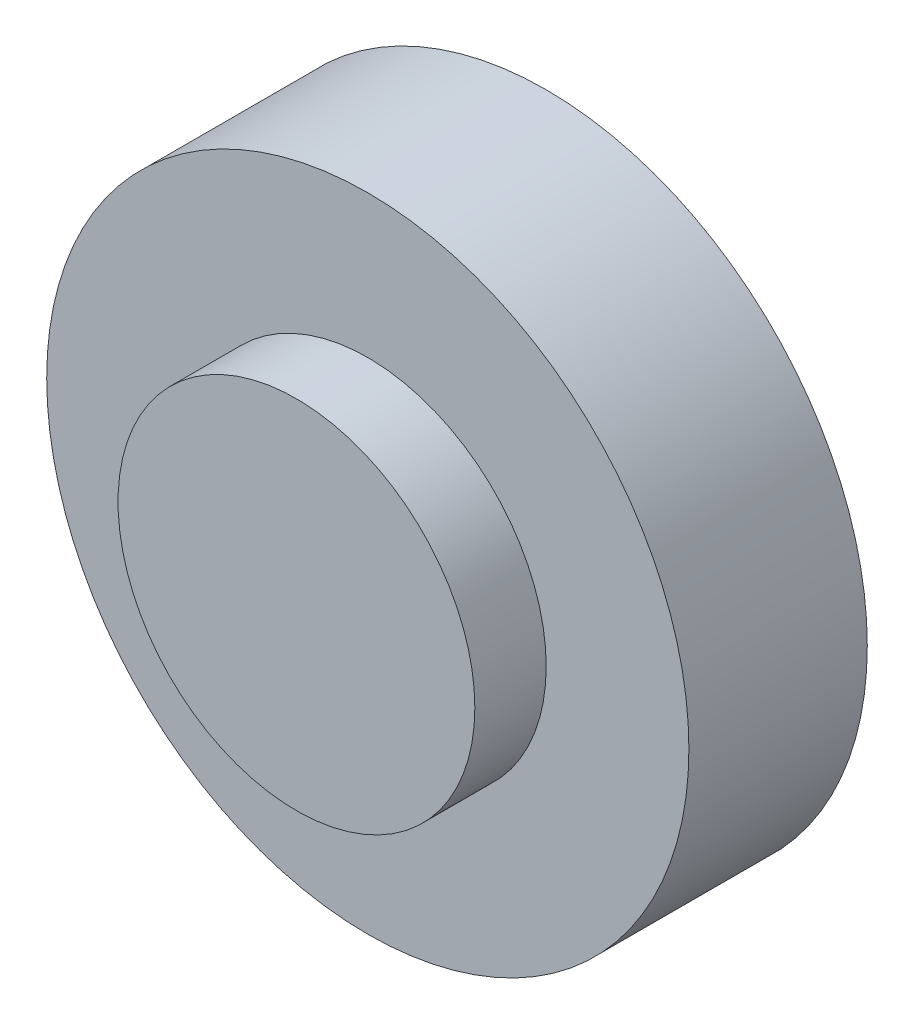
SolidWorks part; units mm, degrees
ref_plane "Спереди" through (0, 0, 0) normal (0, 0, 1) x (1, 0, 0)
ref_plane "Сверху" through (0, 0, 0) normal (0, 1, 0) x (1, 0, 0)
ref_plane "Справа" through (0, 0, 0) normal (1, 0, 0) x (0, 0, -1)
sketch "Эскиз1" plane through (0, 0, 0) normal (0, 0, 1) x (1, 0, 0)
  circle A0 centre (0, 0) radius 45
extrude "Вытянуть1" add sketch "Эскиз1" along normal blind 35
sketch "Эскиз4" plane through (0, 0, 0) normal (0, 0, -1) x (-1, 0, 0)
  circle A0 centre (0, 0) radius 12.5
extrude "Вытянуть3" cut sketch "Эскиз4" against normal blind 25
sketch "Эскиз5" plane through (0, 0, 35) normal (0, 0, 1) x (1, 0, 0)
  circle A0 centre (0, 0) radius 45
  circle A1 centre (0, 0) radius 25
extrude "Вытянуть4" cut sketch "Эскиз5" against normal blind 10
sketch "Эскиз6" plane through (0, 0, 0) normal (0, 0, -1) x (-1, 0, 0)
  circle A0 centre (0, 0) radius 25
extrude "Вытянуть6" cut sketch "Эскиз6" against normal blind 20
